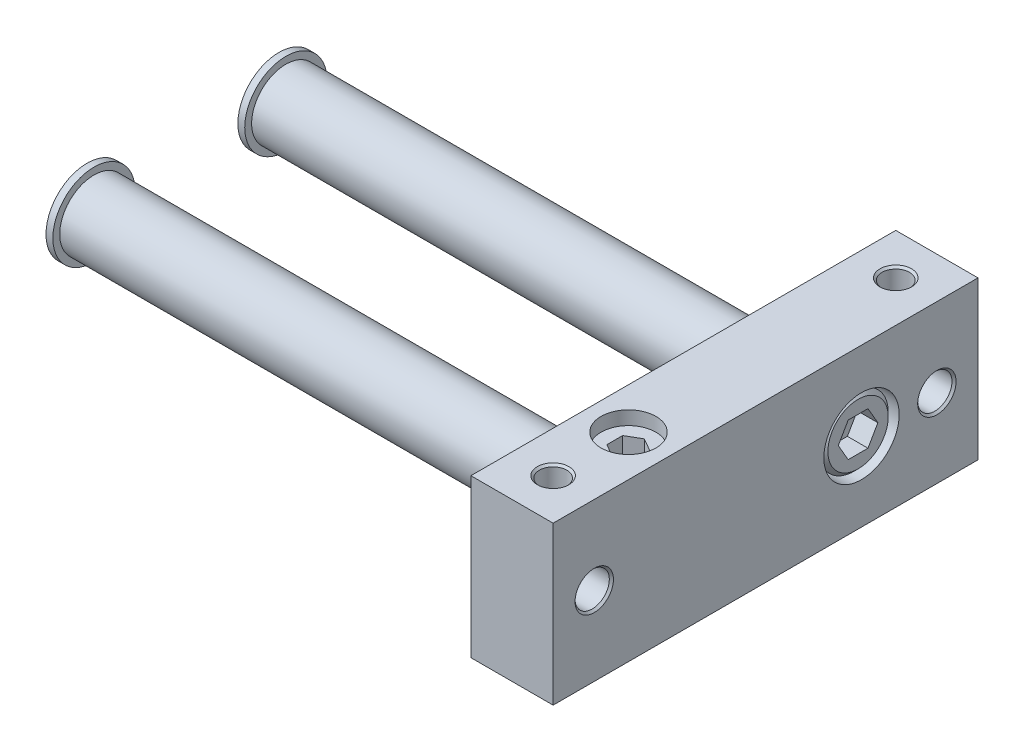
SolidWorks part; units mm, degrees
ref_plane "Plane1" through (0, 0, 0) normal (0, 0, 1) x (1, 0, 0)
ref_plane "Plane2" through (0, 0, 0) normal (0, 1, 0) x (1, 0, 0)
ref_plane "Plane3" through (0, 0, 0) normal (1, 0, 0) x (0, 0, -1)
sketch "Plate_Sketch" plane through (0, 0, 0) normal (1, 0, 0) x (0, 0, -1)
  line L0 (-31, 11.5) -> (-31, -11.5)
  line L1 (-31, -11.5) -> (31, -11.5)
  line L2 (31, -11.5) -> (31, 11.5)
  line L3 (31, 11.5) -> (-31, 11.5)
  line L4 (-24.2, 0) -> (24.2, 0) construction
  line L5 (0, -6.75) -> (0, 9.75) construction
  line L6 (0, 12.5779) -> (0, -12.5779) construction
  line L7 (16.4357, 0) -> (-16.4357, 0) construction
  dimension "C" = 62
  dimension "D" = 23
extrude "Plate" add sketch "Plate_Sketch" along normal blind 12
hole_wizard "Tapped Hole Face" positions "Tapped Hole Face Loc" profile "Tapped Hole Face Profile" tap size "M3x0.5" standard "Ansi Metric" end condition through all
sketch "Tapped Hole Face Loc" plane through (12, 0, 0) normal (1, 0, 0) x (0, 0, -1)
  line L0 (0, 0) -> (0, 21.0226) construction
  line L1 (-31, -11.5) -> (31, -11.5) construction
  point P0 (-25, 0)
  point P1 (25, 0)
  dimension "G" = 50
  dimension "E" = 11.5
sketch "Tapped Hole Face Profile" plane through (12, 0, 25) normal (0, 1, 0) x (0, 0, -1)
  line L0 (0, 0) -> (0, 12)
  line L1 (0, 12) -> (2.5, 12)
  line L2 (2.5, 12) -> (2.5, 0.3)
  line L3 (2.5, 0.3) -> (2.8, 0)
  line L5 (2.8, 0) -> (0, 0)
  line L6 (-2.5, 0.3) -> (-2.8, 0) construction
  line L11 (0, -6.35) -> (0, 107.95) construction
  dimension "Thread Major Dia." = 5
  dimension "Thru Tap Drill Depth" = 12
  dimension "Near CSink Dia." = 5.6
  dimension "Near CSink Angle" = 90
ref_plane "bottom" through (0, -12.5, 0) normal (0, -1, 0) x (1, 0, 0)
ref_plane "innerlimit" through (-12, 0, 0) normal (1, 0, 0) x (0, 0, -1)
ref_plane "strokelimit" through (-62, 0, 0) normal (1, 0, 0) x (0, 0, -1)
sketch "Rods_Sketch" plane through (-12, 0, 0) normal (-1, 0, 0) x (0, 0, 1)
  line L0 (0, -7.7893) -> (0, 7.4105) construction
  line L1 (0, -12.5779) -> (0, 12.5779) construction
  line L3 (-4, -12.5) -> (4, -12.5) construction
  circle A0 centre (-14, 0) radius 5
  circle A1 centre (14, 0) radius 5
  dimension "NN" = 10
  dimension "H" = 28
  dimension "QQ" = 12.5
extrude "Rods" add sketch "Rods_Sketch" along normal blind 60 and the other way up to surface (24 mm away)
sketch "Piston_Sketch" plane through (-72, 0, 0) normal (-1, 0, 0) x (0, 0, 1)
  circle A0 centre (-14, 0) radius 6
  circle A1 centre (14, 0) radius 6
extrude "Piston" add sketch "Piston_Sketch" along normal blind 1
hole_wizard "Tapped Holes Top" positions "Tapped Holes Top Loc" profile "Tapped Holes Top Profile" tap size "M3x0.5" standard "Ansi Metric"
sketch "Tapped Holes Top Loc" plane through (0, 11.5, 0) normal (0, 1, 0) x (-1, 0, 0)
  line L0 (0, 0) -> (-11.3574, 0) construction
  line L2 (-12, -31) -> (-12, 31) construction
  line L3 (0, -25) -> (-11.7, -25) construction
  point P0 (-6, -25)
  point P1 (-6, 25)
  dimension "I" = 6
sketch "Tapped Holes Top Profile" plane through (6, 11.5, -25) normal (1, 0, 0) x (0, 0, 1)
  line L0 (0, 0) -> (0, 6.4998)
  line L1 (0, 6.4998) -> (1.7, 6.2)
  line L2 (1.7, 6.2) -> (1.7, 6)
  line L3 (1.7, 6) -> (2, 6)
  line L5 (2, 6) -> (2, 0.3)
  line L6 (2, 0.3) -> (2.3, 0)
  line L7 (2.3, 0) -> (0, 0)
  line L8 (-2, 0.3) -> (-2.3, 0) construction
  line L10 (0, 6.4998) -> (-1.7, 6.2) construction
  line L11 (0, -6.35) -> (0, 107.95) construction
  dimension "Tap Drill Dia." = 3.4
  dimension "Tap Drill Depth" = 6.2
  dimension "Thread Major Dia." = 4
  dimension "Thread Depth" = 6
  dimension "Near C'Sink Dia." = 4.6
  dimension "Near C'Sink Angle" = 90
  dimension "Drill Angle" = 160
mirror "Tapped Holes Top Mirror" about plane through (0, 0, 0) normal (0, 1, 0) of "Tapped Holes Top"
sketch "SHCS Seat_Sketch" plane through (12, 0, 0) normal (1, 0, 0) x (0, 0, -1)
  circle A0 centre (14, 0) radius 5.5
  circle A1 centre (14, 0) radius 5 construction
  dimension "Dia" = 11
extrude "SHCS Seat" cut sketch "SHCS Seat_Sketch" against normal blind 6.5
sketch "SHCS Head_Sketch" plane through (5.5, 0, 0) normal (1, 0, 0) x (0, 0, -1)
  circle A0 centre (14, 0) radius 5
  circle A1 centre (14, 0) radius 5.5 construction
  dimension "Dia" = 10
extrude "SHCS Head" add sketch "SHCS Head_Sketch" along normal blind 6
sketch "SHCS Hex_Sketch" plane through (11.5, 0, 0) normal (1, 0, 0) x (0, 0, -1)
  line L1 (15.4434, -2.5) -> (16.8868, 0)
  line L2 (16.8868, 0) -> (15.4434, 2.5)
  line L3 (15.4434, 2.5) -> (12.5566, 2.5)
  line L4 (12.5566, 2.5) -> (11.1132, 0)
  line L5 (11.1132, 0) -> (12.5566, -2.5)
  line L6 (12.5566, -2.5) -> (15.4434, -2.5)
  circle A0 centre (14, 0) radius 2.5 construction
  circle A1 centre (14, 0) radius 5 construction
  dimension "Flats" = 5
extrude "SHCS Hex" cut sketch "SHCS Hex_Sketch" against normal blind 3
chamfer "SHCS Cham" distance 0.6 1 edges at (11.5, 0, -19)
sketch "SS Seat_Sketch" plane through (0, 11.5, 0) normal (0, 1, 0) x (-1, 0, 0)
  line L0 (72, 14) -> (0, 14) construction
  circle A0 centre (-6, 14) radius 4
  dimension "Dia" = 8
extrude "SS Seat" cut sketch "SS Seat_Sketch" against normal blind 2
sketch "SS Hex_Sketch" plane through (0, 9.5, 0) normal (0, 1, 0) x (-1, 0, 0)
  line L1 (-8, 12.8453) -> (-6, 11.6906)
  line L2 (-6, 11.6906) -> (-4, 12.8453)
  line L3 (-4, 12.8453) -> (-4, 15.1547)
  line L4 (-4, 15.1547) -> (-6, 16.3094)
  line L5 (-6, 16.3094) -> (-8, 15.1547)
  line L6 (-8, 15.1547) -> (-8, 12.8453)
  circle A0 centre (-6, 14) radius 2 construction
  circle A1 centre (-6, 14) radius 4 construction
  dimension "Flats" = 4
extrude "SS Hex" cut sketch "SS Hex_Sketch" against normal blind 4
